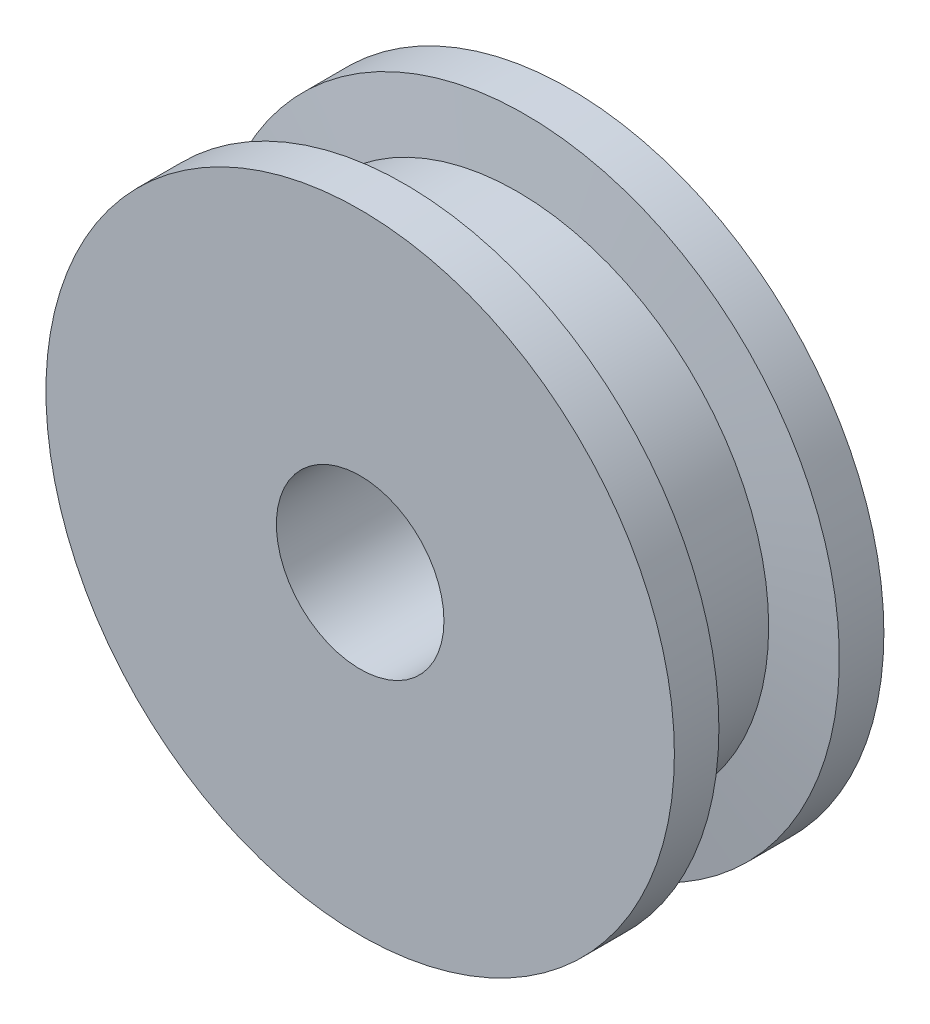
SolidWorks part; units mm, degrees
ref_plane "前视" through (0, 0, 0) normal (0, 0, 1) x (1, 0, 0)
ref_plane "上视" through (0, 0, 0) normal (0, 1, 0) x (1, 0, 0)
ref_plane "右视" through (0, 0, 0) normal (1, 0, 0) x (0, 0, -1)
sketch "草图1" plane through (0, 0, 0) normal (0, 0, 1) x (1, 0, 0)
  circle A0 centre (0, 0) radius 15
  dimension "D1" = 30
extrude "凸台-拉伸1" add sketch "草图1" along normal blind 10
sketch "草图3" plane through (0, 0, 0) normal (0, 1, 0) x (1, 0, 0)
  line L0 (-15, -5) -> (15, -5) construction
  line L1 (-15, 0) -> (-15, -10) construction
  line L2 (15, -10) -> (15, 0) construction
  line L3 (-16, -2) -> (-12, -2.5)
  line L4 (-12, -2.5) -> (-12, -7.5)
  line L5 (-12, -7.5) -> (-16, -8)
  line L6 (-16, -8) -> (-16, -2)
  line L7 (15, 0) -> (-15, 0) construction
  line L8 (-15, -10) -> (15, -10) construction
  line L10 (0, 0) -> (0, -10) construction
  dimension "D1" = 2
  dimension "D2" = 2
  dimension "D3" = 12
  dimension "D4" = 2.5
  dimension "D5" = 2.5
revolve "切除-旋转2" cut sketch "草图3" angle 360 about axis through (0, 0, 10) along (0, 0, -1)
sketch "草图4" plane through (0, 0, 10) normal (0, 0, 1) x (1, 0, 0)
  circle A0 centre (0, 0) radius 4
  dimension "D1" = 8
extrude "切除-拉伸1" cut sketch "草图4" against normal through all
